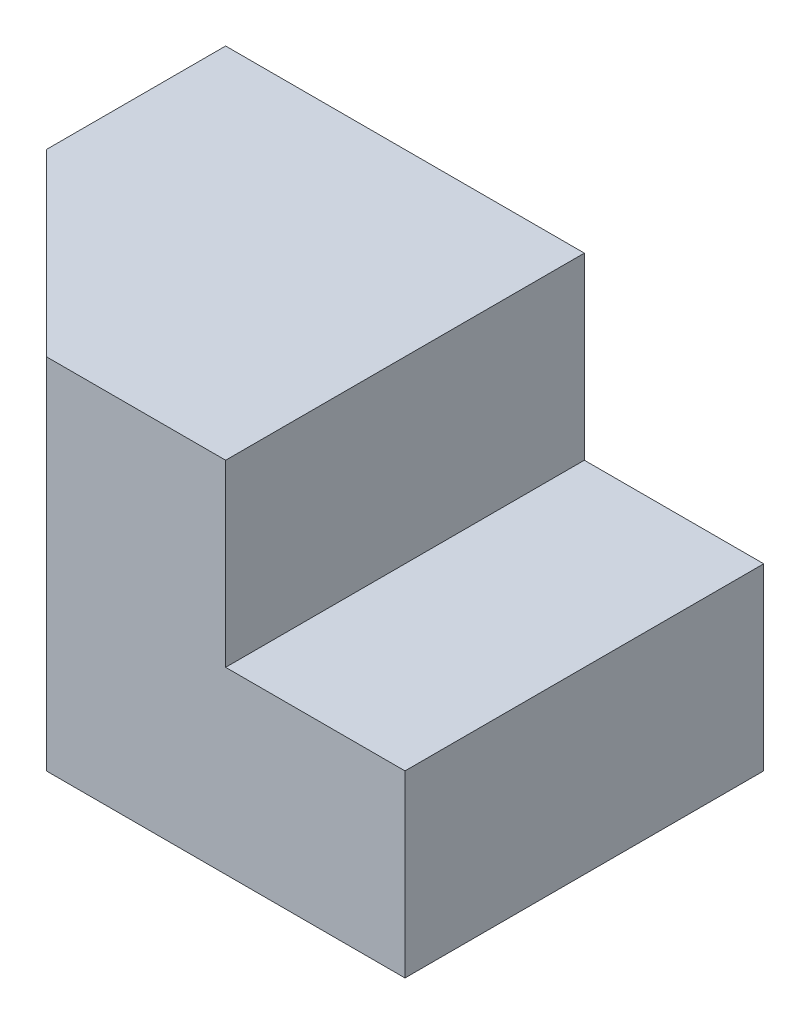
SolidWorks part; units mm, degrees
ref_plane "Front Plane" through (0, 0, 0) normal (0, 0, 1) x (1, 0, 0)
ref_plane "Top Plane" through (0, 0, 0) normal (0, 1, 0) x (1, 0, 0)
ref_plane "Right Plane" through (0, 0, 0) normal (1, 0, 0) x (0, 0, -1)
sketch "Sketch1" plane through (0, 0, 0) normal (0, 0, 1) x (1, 0, 0)
  line L1 (-59.0958, 19.132) -> (0.9042, 19.132)
  line L2 (-59.0958, 19.132) -> (-59.0958, -20.868)
  line L3 (-59.0958, -20.868) -> (0.9042, -20.868)
  line L4 (0.9042, 19.132) -> (0.9042, -20.868)
  line L5 (0.9042, 19.132) -> (-19.0958, 19.132)
  line L6 (0.9042, 19.132) -> (0.9042, -0.868)
  line L7 (0.9042, -0.868) -> (-19.0958, -0.868)
  line L8 (-19.0958, 19.132) -> (-19.0958, -0.868)
  dimension "D1" = 60
  dimension "D2" = 40
  dimension "D3" = 20
  dimension "D4" = 20
extrude "Boss-Extrude1" add sketch "Sketch1" along normal blind 40 contours L8 L1 L2 L3 L4 L7
sketch "Sketch2" plane through (0, 19.132, 0) normal (0, 1, 0) x (1, 0, 0)
  line L0 (-59.0958, -40) -> (-39.0958, -40)
  line L1 (-59.0958, -40) -> (-19.0958, -40) construction
  line L2 (-39.0958, -40) -> (-59.0958, -20)
  line L3 (-59.0958, -40) -> (-59.0958, 0) construction
  line L4 (-59.0958, -20) -> (-59.0958, -40)
  dimension "D1" = 20
  dimension "20" = 20
extrude "Cut-Extrude1" cut sketch "Sketch2" against normal blind 40
